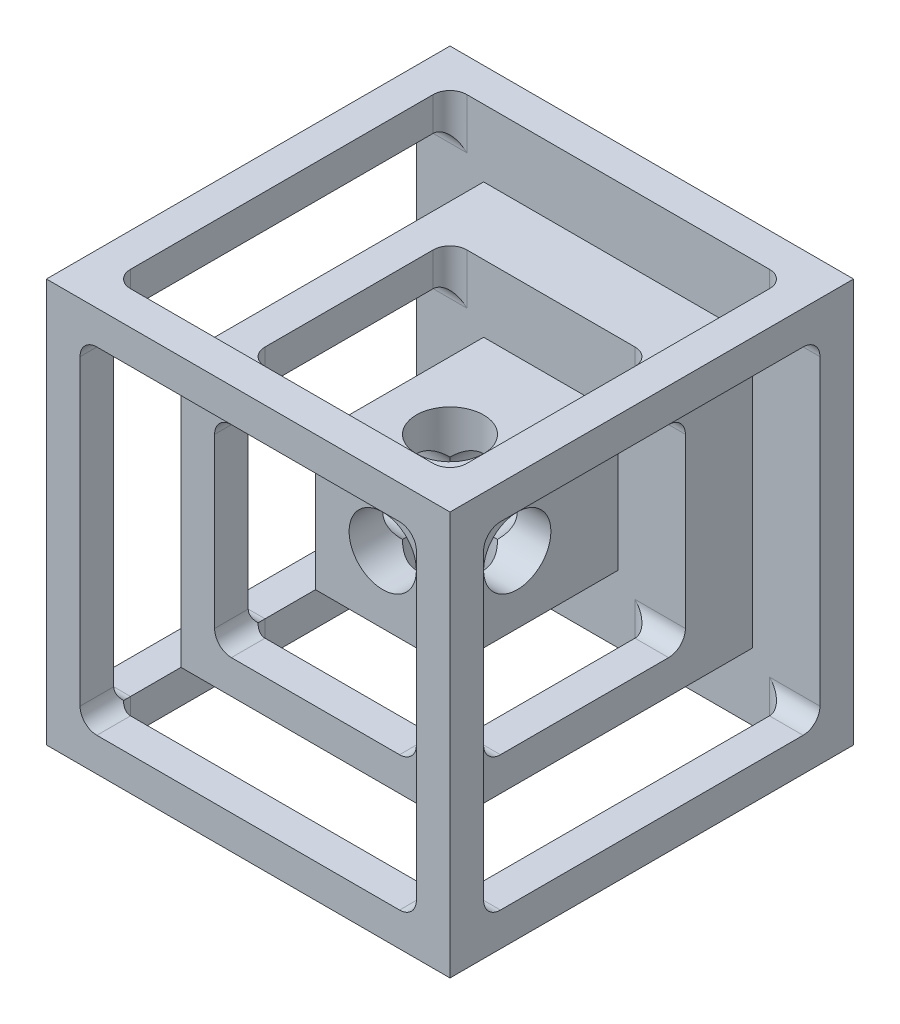
SolidWorks part; units mm, degrees
ref_plane "Front Plane" through (0, 0, 0) normal (0, 0, 1) x (1, 0, 0)
ref_plane "Top Plane" through (0, 0, 0) normal (0, 1, 0) x (1, 0, 0)
ref_plane "Right Plane" through (0, 0, 0) normal (1, 0, 0) x (0, 0, -1)
sketch "Sketch1" plane through (0, 0, 0) normal (0, 1, 0) x (1, 0, 0)
  line L1 (0, 0) -> (152.4, 0)
  line L2 (0, 0) -> (0, 152.4)
  line L3 (0, 152.4) -> (152.4, 152.4)
  line L4 (152.4, 0) -> (152.4, 152.4)
extrude "Extrude2" add sketch "Sketch1" along normal blind 152.4
sketch "Sketch13" plane through (0, 152.4, 0) normal (0, 1, 0) x (1, 0, 0)
  line L1 (19.05, 12.7) -> (133.35, 12.7)
  line L2 (12.7, 19.05) -> (12.7, 133.35)
  line L3 (19.05, 139.7) -> (133.35, 139.7)
  line L4 (139.7, 19.05) -> (139.7, 133.35)
  arc A0 (139.7, 19.05) -> (133.35, 12.7) centre (133.35, 19.05) cw
  arc A1 (12.7, 19.05) -> (19.05, 12.7) centre (19.05, 19.05) ccw
  arc A2 (19.05, 139.7) -> (12.7, 133.35) centre (19.05, 133.35) ccw
  arc A3 (139.7, 133.35) -> (133.35, 139.7) centre (133.35, 133.35) ccw
  point P9 (12.7, 12.7)
  dimension "D3" = 6.35
  dimension "D1" = 114.3
  dimension "D2" = 114.3
extrude "Cut-Extrude14" cut sketch "Sketch13" against normal blind 25.4
sketch "Sketch17" plane through (0, 0, 0) normal (0, 0, 1) x (1, 0, 0)
  line L1 (19.05, 12.7) -> (133.35, 12.7)
  line L2 (12.7, 19.05) -> (12.7, 133.35)
  line L3 (19.05, 139.7) -> (133.35, 139.7)
  line L4 (139.7, 19.05) -> (139.7, 133.35)
  arc A0 (139.7, 19.05) -> (133.35, 12.7) centre (133.35, 19.05) cw
  arc A1 (12.7, 19.05) -> (19.05, 12.7) centre (19.05, 19.05) ccw
  arc A2 (19.05, 139.7) -> (12.7, 133.35) centre (19.05, 133.35) ccw
  arc A3 (139.7, 133.35) -> (133.35, 139.7) centre (133.35, 133.35) ccw
  point P9 (12.7, 12.7)
  dimension "D3" = 6.35
  dimension "D1" = 114.3
  dimension "D2" = 114.3
extrude "Cut-Extrude18" cut sketch "Sketch17" against normal blind 25.4
sketch "Sketch18" plane through (152.4, 0, 0) normal (1, 0, 0) x (0, 0, -1)
  line L1 (19.05, 12.7) -> (133.35, 12.7)
  line L2 (12.7, 19.05) -> (12.7, 133.35)
  line L3 (19.05, 139.7) -> (133.35, 139.7)
  line L4 (139.7, 19.05) -> (139.7, 133.35)
  arc A0 (139.7, 19.05) -> (133.35, 12.7) centre (133.35, 19.05) cw
  arc A1 (12.7, 19.05) -> (19.05, 12.7) centre (19.05, 19.05) ccw
  arc A2 (19.05, 139.7) -> (12.7, 133.35) centre (19.05, 133.35) ccw
  arc A3 (139.7, 133.35) -> (133.35, 139.7) centre (133.35, 133.35) ccw
  point P9 (12.7, 12.7)
  dimension "D3" = 6.35
  dimension "D1" = 114.3
  dimension "D2" = 114.3
extrude "Cut-Extrude19" cut sketch "Sketch18" against normal blind 25.4
sketch "Sketch20" plane through (0, 0, 0) normal (-1, 0, 0) x (0, 0, 1)
  line L1 (-133.35, 12.7) -> (-19.05, 12.7)
  line L2 (-139.7, 19.05) -> (-139.7, 133.35)
  line L3 (-133.35, 139.7) -> (-19.05, 139.7)
  line L4 (-12.7, 19.05) -> (-12.7, 133.35)
  arc A0 (-12.7, 19.05) -> (-19.05, 12.7) centre (-19.05, 19.05) cw
  arc A1 (-139.7, 19.05) -> (-133.35, 12.7) centre (-133.35, 19.05) ccw
  arc A2 (-133.35, 139.7) -> (-139.7, 133.35) centre (-133.35, 133.35) ccw
  arc A3 (-12.7, 133.35) -> (-19.05, 139.7) centre (-19.05, 133.35) ccw
  point P9 (-139.7, 12.7)
  dimension "D3" = 6.35
  dimension "D1" = 114.3
  dimension "D2" = 114.3
extrude "Cut-Extrude21" cut sketch "Sketch20" against normal blind 25.4
sketch "Sketch21" plane through (0, 0, 0) normal (0, -1, 0) x (1, 0, 0)
  line L1 (19.05, -139.7) -> (133.35, -139.7)
  line L2 (12.7, -133.35) -> (12.7, -19.05)
  line L3 (19.05, -12.7) -> (133.35, -12.7)
  line L4 (139.7, -133.35) -> (139.7, -19.05)
  arc A0 (139.7, -133.35) -> (133.35, -139.7) centre (133.35, -133.35) cw
  arc A1 (12.7, -133.35) -> (19.05, -139.7) centre (19.05, -133.35) ccw
  arc A2 (19.05, -12.7) -> (12.7, -19.05) centre (19.05, -19.05) ccw
  arc A3 (139.7, -19.05) -> (133.35, -12.7) centre (133.35, -19.05) ccw
  point P9 (12.7, -139.7)
  dimension "D3" = 6.35
  dimension "D1" = 114.3
  dimension "D2" = 114.3
extrude "Cut-Extrude22" cut sketch "Sketch21" against normal blind 25.4
sketch "Sketch23" plane through (0, 0, -25.4) normal (0, 0, 1) x (1, 0, 0)
  line L0 (25.4, 25.4) -> (127, 25.4) construction
  line L1 (44.45, 38.1) -> (107.95, 38.1)
  line L2 (38.1, 44.45) -> (38.1, 107.95)
  line L3 (44.45, 114.3) -> (107.95, 114.3)
  line L4 (114.3, 44.45) -> (114.3, 107.95)
  line L5 (25.4, 127) -> (25.4, 25.4) construction
  arc A0 (38.1, 44.45) -> (44.45, 38.1) centre (44.45, 44.45) ccw
  arc A1 (44.45, 114.3) -> (38.1, 107.95) centre (44.45, 107.95) ccw
  arc A2 (107.95, 38.1) -> (114.3, 44.45) centre (107.95, 44.45) ccw
  arc A3 (114.3, 107.95) -> (107.95, 114.3) centre (107.95, 107.95) ccw
  dimension "D1" = 6.35
  dimension "D2" = 76.2
  dimension "D3" = 76.2
  dimension "D4" = 19.05
  dimension "D5" = 19.05
extrude "Cut-Extrude24" cut sketch "Sketch23" against normal blind 25.4
sketch "Sketch26" plane through (0, 25.4, 0) normal (0, -1, 0) x (1, 0, 0)
  line L1 (44.45, -114.3) -> (107.95, -114.3)
  line L2 (38.1, -107.95) -> (38.1, -44.45)
  line L3 (44.45, -38.1) -> (107.95, -38.1)
  line L4 (114.3, -107.95) -> (114.3, -44.45)
  line L5 (25.4, -25.4) -> (127, -25.4) construction
  line L6 (25.4, -139.7) -> (25.4, -25.4) construction
  arc A0 (38.1, -107.95) -> (44.45, -114.3) centre (44.45, -107.95) ccw
  arc A1 (44.45, -38.1) -> (38.1, -44.45) centre (44.45, -44.45) ccw
  arc A2 (107.95, -114.3) -> (114.3, -107.95) centre (107.95, -107.95) ccw
  arc A3 (114.3, -44.45) -> (107.95, -38.1) centre (107.95, -44.45) ccw
  dimension "D1" = 6.35
  dimension "D2" = 76.2
  dimension "D3" = 76.2
  dimension "D4" = 19.05
  dimension "D5" = 19.05
extrude "Cut-Extrude27" cut sketch "Sketch26" against normal blind 25.4
sketch "Sketch27" plane through (0, 127, 0) normal (0, 1, 0) x (-1, 0, 0)
  line L0 (-127, -25.4) -> (-127, -139.7) construction
  line L1 (-107.95, -114.3) -> (-44.45, -114.3)
  line L2 (-114.3, -107.95) -> (-114.3, -44.45)
  line L3 (-107.95, -38.1) -> (-44.45, -38.1)
  line L4 (-38.1, -107.95) -> (-38.1, -44.45)
  line L7 (-127, -139.7) -> (-25.4, -139.7) construction
  arc A0 (-114.3, -107.95) -> (-107.95, -114.3) centre (-107.95, -107.95) ccw
  arc A1 (-107.95, -38.1) -> (-114.3, -44.45) centre (-107.95, -44.45) ccw
  arc A2 (-44.45, -114.3) -> (-38.1, -107.95) centre (-44.45, -107.95) ccw
  arc A3 (-38.1, -44.45) -> (-44.45, -38.1) centre (-44.45, -44.45) ccw
  dimension "D1" = 6.35
  dimension "D2" = 76.2
  dimension "D3" = 76.2
  dimension "D4" = 19.05
  dimension "D5" = 25.4
extrude "Cut-Extrude28" cut sketch "Sketch27" against normal blind 25.4
sketch "Sketch28" plane through (25.4, 0, 0) normal (-1, 0, 0) x (0, -1, 0)
  line L0 (-127, -139.7) -> (-25.4, -139.7) construction
  line L1 (-107.95, -114.3) -> (-44.45, -114.3)
  line L2 (-114.3, -107.95) -> (-114.3, -44.45)
  line L3 (-107.95, -38.1) -> (-44.45, -38.1)
  line L4 (-38.1, -107.95) -> (-38.1, -44.45)
  line L7 (-127, -139.7) -> (-127, -25.4) construction
  arc A0 (-114.3, -107.95) -> (-107.95, -114.3) centre (-107.95, -107.95) ccw
  arc A1 (-107.95, -38.1) -> (-114.3, -44.45) centre (-107.95, -44.45) ccw
  arc A2 (-44.45, -114.3) -> (-38.1, -107.95) centre (-44.45, -107.95) ccw
  arc A3 (-38.1, -44.45) -> (-44.45, -38.1) centre (-44.45, -44.45) ccw
  dimension "D1" = 6.35
  dimension "D2" = 76.2
  dimension "D3" = 76.2
  dimension "D4" = 25.4
  dimension "D5" = 19.05
extrude "Cut-Extrude29" cut sketch "Sketch28" against normal blind 25.4
sketch "Sketch29" plane through (127, 0, 0) normal (1, 0, 0) x (0, 1, 0)
  line L1 (44.45, -114.3) -> (107.95, -114.3)
  line L2 (38.1, -107.95) -> (38.1, -44.45)
  line L3 (44.45, -38.1) -> (107.95, -38.1)
  line L4 (114.3, -107.95) -> (114.3, -44.45)
  line L7 (25.4, -25.4) -> (127, -25.4) construction
  line L8 (25.4, -25.4) -> (25.4, -139.7) construction
  arc A0 (38.1, -107.95) -> (44.45, -114.3) centre (44.45, -107.95) ccw
  arc A1 (44.45, -38.1) -> (38.1, -44.45) centre (44.45, -44.45) ccw
  arc A2 (107.95, -114.3) -> (114.3, -107.95) centre (107.95, -107.95) ccw
  arc A3 (114.3, -44.45) -> (107.95, -38.1) centre (107.95, -44.45) ccw
  dimension "D1" = 6.35
  dimension "D2" = 76.2
  dimension "D3" = 76.2
  dimension "D4" = 19.05
  dimension "D5" = 19.05
extrude "Cut-Extrude30" cut sketch "Sketch29" against normal blind 25.4
sketch "Sketch30" plane through (0, 0, -50.8) normal (0, 0, 1) x (1, 0, 0)
  circle A0 centre (76.2, 76.2) radius 12.7
extrude "Cut-Extrude31" cut sketch "Sketch30" against normal through all
sketch "Sketch31" plane through (101.6, 0, 0) normal (1, 0, 0) x (0, 0, -1)
  circle A0 centre (76.2, 76.2) radius 12.7
extrude "Cut-Extrude32" cut sketch "Sketch31" against normal through all
sketch "Sketch32" plane through (0, 50.8, 0) normal (0, -1, 0) x (1, 0, 0)
  circle A0 centre (76.2, -76.2) radius 12.7
extrude "Cut-Extrude33" cut sketch "Sketch32" against normal through all
scale "Scale1" scale about centroid uniform scaling yes scale factor 2
